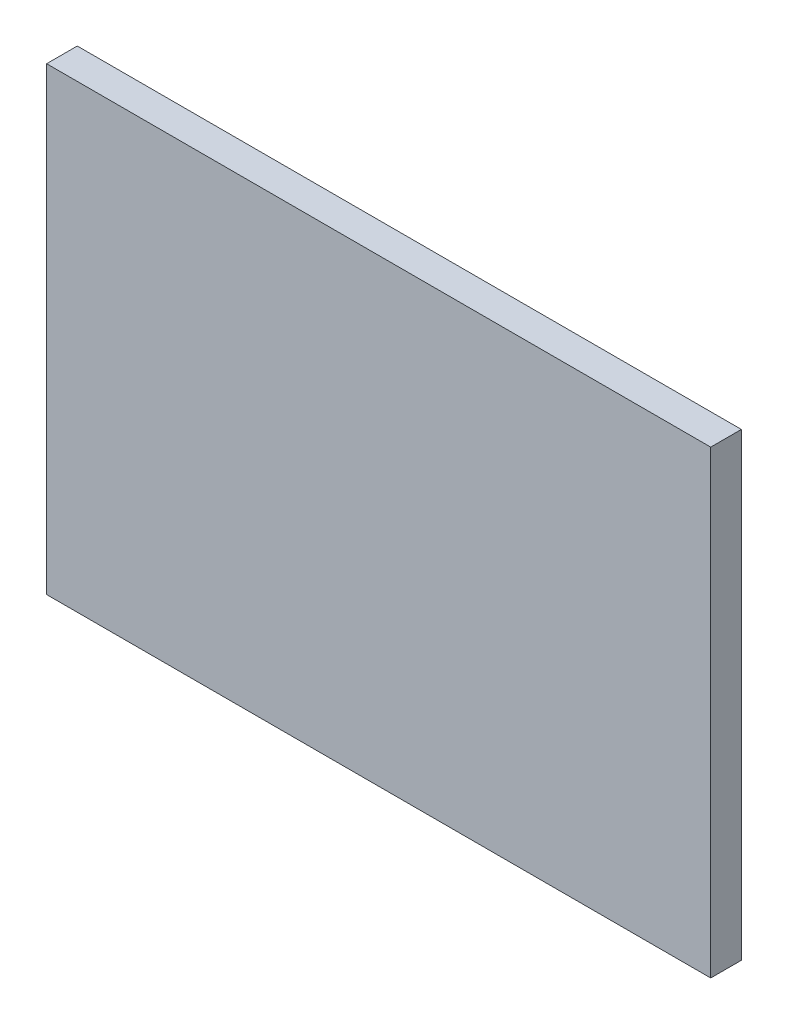
SolidWorks part; units mm, degrees
ref_plane "前视基准面" through (0, 0, 0) normal (0, 0, 1) x (1, 0, 0)
ref_plane "上视基准面" through (0, 0, 0) normal (0, 1, 0) x (1, 0, 0)
ref_plane "右视基准面" through (0, 0, 0) normal (1, 0, 0) x (0, 0, -1)
sketch "草图1" plane through (0, 0, 0) normal (0, 1, 0) x (1, 0, 0)
  line L1 (-58.2415, 28.3212) -> (6.7585, 28.3212)
  line L2 (-58.2415, 28.3212) -> (-58.2415, 31.3212)
  line L3 (-58.2415, 31.3212) -> (6.7585, 31.3212)
  line L4 (6.7585, 28.3212) -> (6.7585, 31.3212)
  dimension "D1" = 65
  dimension "D2" = 3
extrude "凸台-拉伸1" add sketch "草图1" along normal blind 45
